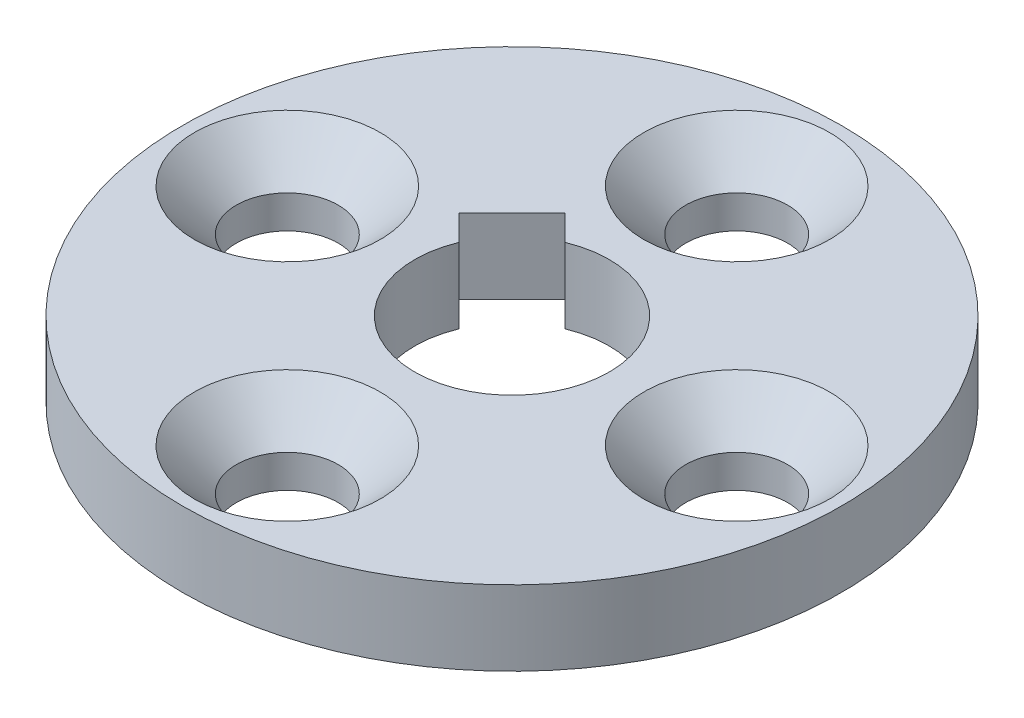
SolidWorks part; units mm, degrees
ref_plane "Front Plane" through (0, 0, 0) normal (0, 0, 1) x (1, 0, 0)
ref_plane "Top Plane" through (0, 0, 0) normal (0, 1, 0) x (1, 0, 0)
ref_plane "Right Plane" through (0, 0, 0) normal (1, 0, 0) x (0, 0, -1)
sketch "Sketch1" plane through (0, 0, 0) normal (0, 1, 0) x (1, 0, 0)
  circle A0 centre (0, 0) radius 11
  dimension "D1" = 22
extrude "Boss-Extrude1" add sketch "Sketch1" along normal blind 2.5
hole_wizard "CSK for M3 socket countersunk head screw1" positions "Sketch2" profile "Sketch3" countersink size "M3" standard "DIN" end condition up to next
sketch "Sketch2" plane through (0, 2.5, 0) normal (0, 1, 0) x (1, 0, 0)
  circle A0 centre (0, 0) radius 7.5 construction
  point P9 (0, 7.5)
  point P17 (7.5, 0)
  point P18 (0, -7.5)
  point P19 (-7.5, 0)
  dimension "D1" = 15
  dimension "D2" = 4
sketch "Sketch3" plane through (-7.5, 2.5, 0) normal (1, 0, 0) x (0, 0, 1)
  line L0 (0, 0) -> (0, 2.5)
  line L1 (0, 2.5) -> (1.7, 2.5)
  line L2 (1.7, 2.5) -> (1.7, 1.4)
  line L3 (1.7, 1.4) -> (3.1, 0)
  line L5 (3.1, 0) -> (0, 0)
  line L6 (-1.7, 1.4) -> (-3.1, 0) construction
  line L11 (0, -6.35) -> (0, 107.95) construction
  dimension "Thru Hole Dia." = 3.4
  dimension "Thru Hole Depth" = 2.5
  dimension "Near C'Sink Dia." = 6.2
  dimension "Near C'Sink Angle" = 90
sketch "Sketch4" plane through (0, 2.5, 0) normal (0, 1, 0) x (1, 0, 0)
  line L0 (0, 0) -> (-2.1213, 2.1213) construction
  line L1 (-2.1213, 2.1213) -> (-2.9698, 2.9698) construction
  line L2 (-3.8537, 2.086) -> (-2.086, 3.8537)
  line L3 (-2.086, 3.8537) -> (-1.0445, 2.8123)
  line L4 (-3.8537, 2.086) -> (-2.8123, 1.0445)
  circle A0 centre (0, 0) radius 3 construction
  circle A1 centre (0, 0) radius 3.25
  point P8 (-2.9698, 2.9698)
  dimension "D1" = 6
  dimension "D4" = 6.5
  dimension "D2" = 1.2
  dimension "D3" = 1.25
extrude "Cut-Extrude1" cut sketch "Sketch4" against normal through all
